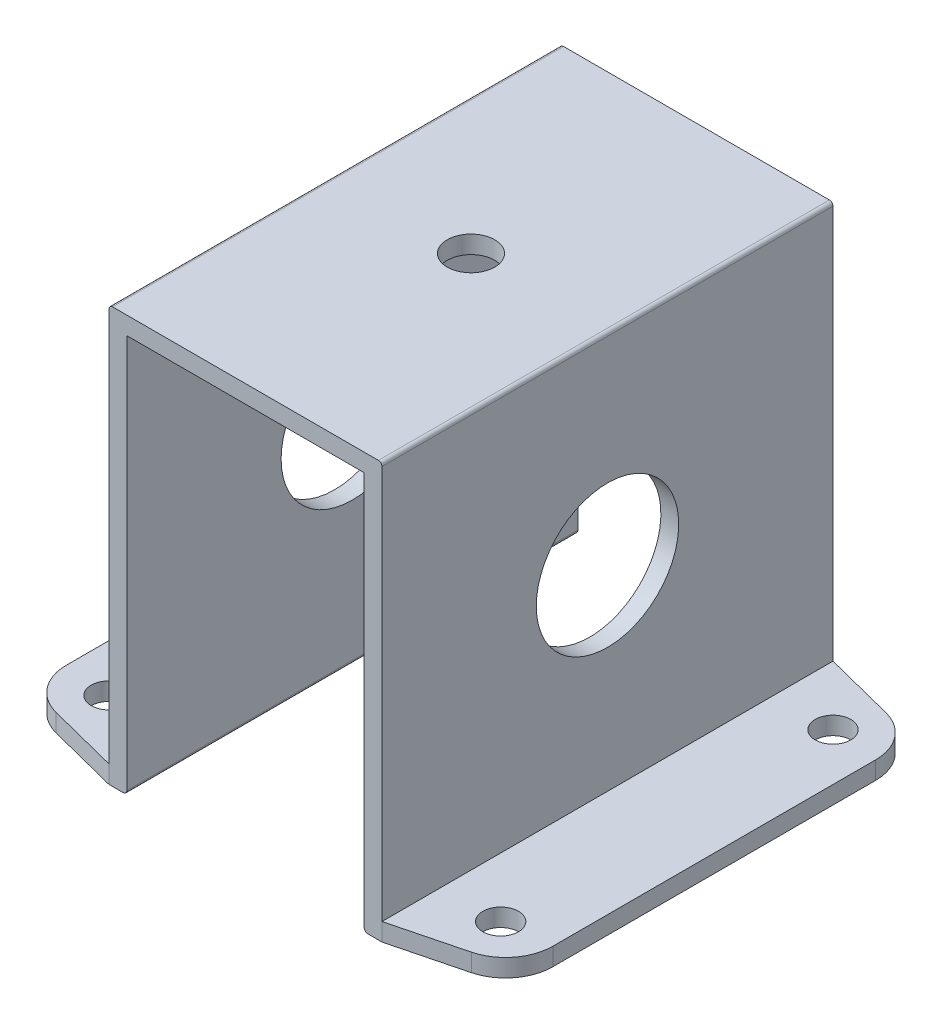
SolidWorks part; units mm, degrees
ref_plane "Front Plane" through (0, 0, 0) normal (0, 0, 1) x (1, 0, 0)
ref_plane "Top Plane" through (0, 0, 0) normal (0, 1, 0) x (1, 0, 0)
ref_plane "Right Plane" through (0, 0, 0) normal (1, 0, 0) x (0, 0, -1)
sketch "Sketch1" plane through (0, 0, 0) normal (0, 0, 1) x (1, 0, 0)
  line L0 (0, 0) -> (0, 7.5833) construction
  line L1 (-10, 0) -> (-10, 33.5)
  line L2 (-10, 33.5) -> (10, 33.5)
  line L3 (10, 33.5) -> (10, 0)
  line L4 (10, 0) -> (11.5, 0)
  line L5 (11.5, 0) -> (11.5, 35)
  line L6 (11.5, 35) -> (-11.5, 35)
  line L7 (-11.5, 35) -> (-11.5, 0)
  line L8 (-11.5, 0) -> (-10, 0)
  dimension "D1" = 1.5
  dimension "D2" = 1.5
  dimension "D3" = 1.5
  dimension "D4" = 20
  dimension "D5" = 10
  dimension "D6" = 35
extrude "Boss-Extrude1" add sketch "Sketch1" along normal mid plane 38
sketch "Sketch3" plane through (0, 0, 0) normal (0, 1, 0) x (1, 0, 0)
  line L0 (-11.5, 19) -> (-17.4904, 17.4691)
  line L1 (-20.5, 13.5937) -> (-20.5, -13.5937)
  line L2 (-17.4904, -17.4691) -> (-11.5, -19)
  line L3 (-11.5, -19) -> (-11.5, 19)
  line L4 (0, 0) -> (0, 1)
  line L5 (17.4904, -17.4691) -> (11.5, -19)
  line L6 (20.5, 13.5937) -> (20.5, -13.5937)
  line L7 (11.5, 19) -> (17.4904, 17.4691)
  line L8 (11.5, -19) -> (11.5, 19)
  line L9 (0, -19.25) -> (0, 19.25) construction
  arc A0 (-17.4904, 17.4691) -> (-20.5, 13.5937) centre (-16.5, 13.5937) ccw
  arc A1 (-17.4904, -17.4691) -> (-20.5, -13.5937) centre (-16.5, -13.5937) cw
  arc A2 (20.5, 13.5937) -> (17.4904, 17.4691) centre (16.5, 13.5937) ccw
  arc A3 (17.4904, -17.4691) -> (20.5, -13.5937) centre (16.5, -13.5937) ccw
  circle A8 centre (-16.5, 14) radius 1.5
  circle A9 centre (-16.5, -14) radius 1.5
  circle A10 centre (16.5, -14) radius 1.5
  circle A11 centre (16.5, 14) radius 1.5
  point P15 (-20.5, 16.7)
  point P18 (-20.5, -16.7)
  point P21 (20.5, 16.7)
  point P24 (20.5, -16.7)
  dimension "D3" = 4
  dimension "D4" = 4
  dimension "D5" = 4
  dimension "D6" = 4
  dimension "D7" = 3
  dimension "D8" = 3
  dimension "D1" = 16.7
  dimension "D2" = 16.7
  dimension "D11" = 16.5
  dimension "D12" = 1
  dimension "D13" = 28
  dimension "D14" = 14
  dimension "D15" = 16.5
sketch "Sketch4" plane through (0, 35, 0) normal (0, 1, 0) x (1, 0, 0)
  circle A0 centre (0, 0) radius 2
  dimension "D1" = 4
extrude "Cut-Extrude1" cut sketch "Sketch4" against normal blind 1.5
sketch "Sketch6" plane through (11.5, 0, 0) normal (1, 0, 0) x (0, 0, -1)
fillet "Fillet1" radius 0.3 1 edges at (-10, 0, 0)
fillet "Fillet2" radius 0.3 1 edges at (10, 0, 0)
fillet "Fillet3" radius 0.3 2 edges at (11.5, 35, 0) (-11.5, 35, 0)
extrude "Boss-Extrude2" add sketch "Sketch3" along normal blind 1.5 contours A1 L2 L3 L0 A0 L1 A9 A8 | L5 A3 L6 A2 L7 L8 A10 A11
sketch "Sketch7" plane through (-11.5, 0, 0) normal (-1, 0, 0) x (0, 0, 1)
  line L0 (-19, 34.7) -> (-19, 1.5) construction
  circle A0 centre (0, 18) radius 6
  dimension "D3" = 12
  dimension "D1" = 18
  dimension "D2" = 19
extrude "Cut-Extrude2" cut sketch "Sketch7" against normal through all
